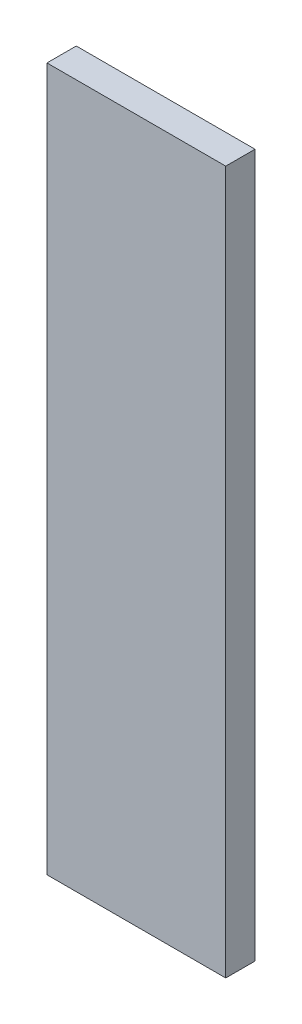
SolidWorks part; units mm, degrees
ref_plane "Front" through (0, 0, 0) normal (0, 0, 1) x (1, 0, 0)
ref_plane "Top" through (0, 0, 0) normal (0, 1, 0) x (1, 0, 0)
ref_plane "Right" through (0, 0, 0) normal (1, 0, 0) x (0, 0, -1)
sketch "Sketch1" plane through (0, 0, 0) normal (0, 0, 1) x (1, 0, 0)
  line L1 (-467.9121, 58.5771) -> (-429.1644, 58.5771)
  line L3 (-467.9121, 210.9771) -> (-429.1644, 210.9771)
  line L4 (-429.1644, 58.5771) -> (-429.1644, 210.9771)
  line L7 (-429.1644, 205.7828) -> (-429.1644, 212.1328) construction
  line L11 (-460.889, 58.5771) -> (-515.3948, 58.5771) construction
  line L13 (-515.3948, 210.9771) -> (-460.889, 210.9771) construction
  line L14 (-467.9121, 58.5771) -> (-467.9121, 210.9771)
  point P0 (0, 0)
  point P10 (0, 0)
extrude "Boss-Extrude1" add sketch "Sketch1" along normal blind 6.35 contours L1 L4 L3 L14
